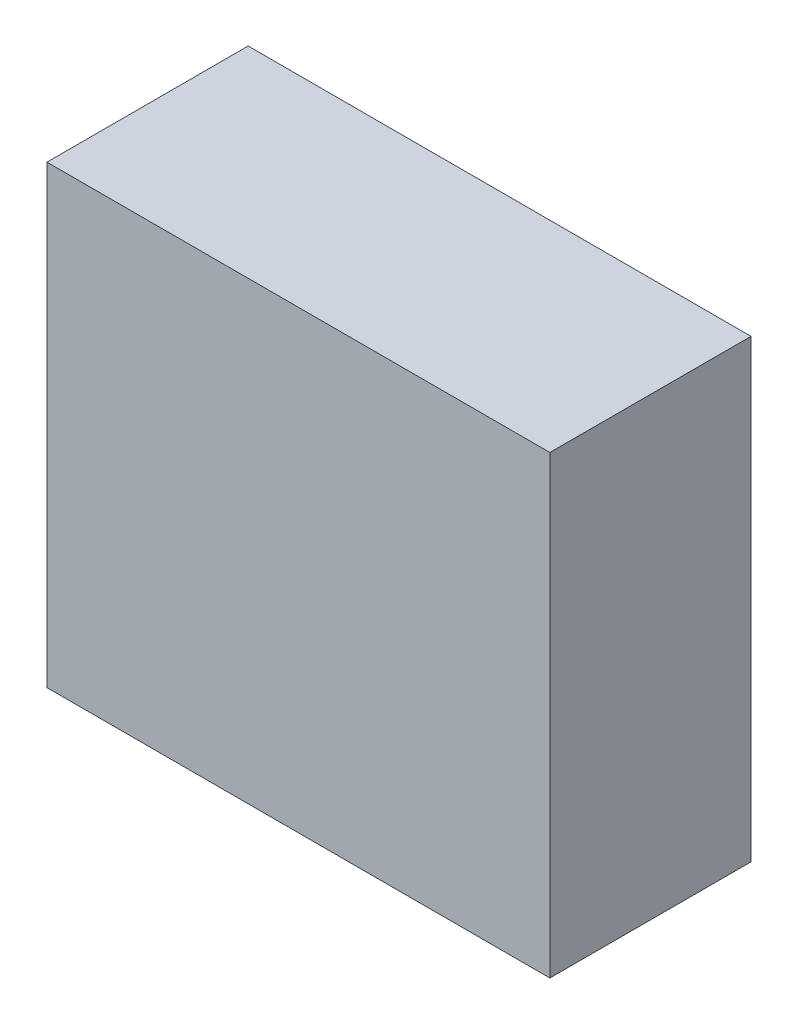
SolidWorks part; units mm, degrees
ref_plane "Front Plane" through (0, 0, 0) normal (0, 0, 1) x (1, 0, 0)
ref_plane "Top Plane" through (0, 0, 0) normal (0, 1, 0) x (1, 0, 0)
ref_plane "Right Plane" through (0, 0, 0) normal (1, 0, 0) x (0, 0, -1)
sketch "Sketch1" plane through (0, 0, 0) normal (0, 0, 1) x (1, 0, 0)
  line L1 (-12.6331, -10.9339) -> (7.3669, -10.9339)
  line L2 (-12.6331, -10.9339) -> (-12.6331, 7.1661)
  line L3 (-12.6331, 7.1661) -> (7.3669, 7.1661)
  line L4 (7.3669, -10.9339) -> (7.3669, 7.1661)
  dimension "D1" = 18.1
  dimension "D2" = 20
extrude "Boss-Extrude1" add sketch "Sketch1" along normal blind 8
